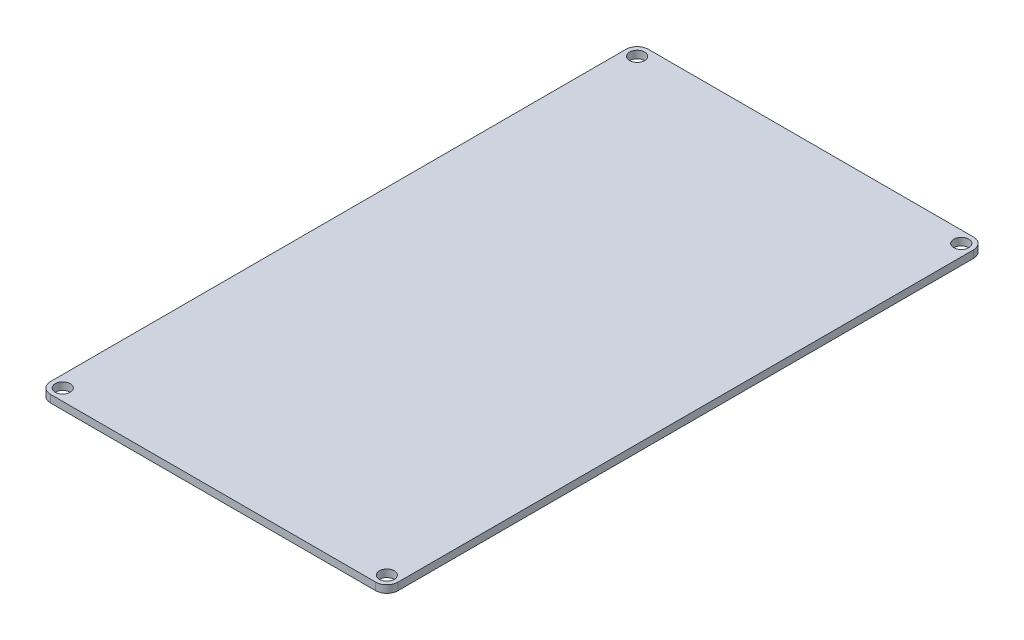
SolidWorks part; units mm, degrees
ref_plane "Front Plane" through (0, 0, 0) normal (0, 0, 1) x (1, 0, 0)
ref_plane "Top Plane" through (0, 0, 0) normal (0, 1, 0) x (1, 0, 0)
ref_plane "Right Plane" through (0, 0, 0) normal (1, 0, 0) x (0, 0, -1)
sketch "Sketch2" plane through (0, 0, 0) normal (0, 1, 0) x (1, 0, 0)
  line L1 (0, 0) -> (93, 0)
  line L2 (0, 0) -> (0, 37.5)
  line L12 (93, 0) -> (93, 160)
  line L17 (95, -2) -> (95, 162)
  line L18 (93, 0) -> (59, 0)
  line L20 (0, 37.5) -> (0, 137.5)
  line L21 (-2, 162) -> (95, 162)
  line L22 (-2, 137.5) -> (-2, 162)
  line L26 (-2, 37.5) -> (-2, 137.5)
  line L28 (0, 137.5) -> (0, 160)
  line L29 (0, 160) -> (93, 160)
  line L34 (-2, -2) -> (-2, 37.5)
  line L43 (-2, -2) -> (95, -2)
  line L44 (46.5, 0) -> (46.5, 160) construction
  line L79 (3.121, 3.121) -> (0, 3.121) construction
  line L80 (3.121, 3.121) -> (3.121, 0) construction
  circle A9 centre (3.121, 3.121) radius 2
  circle A13 centre (89.879, 3.121) radius 2
  circle A14 centre (3.121, 156.879) radius 2
  circle A29 centre (89.879, 156.879) radius 2
  point P41 (2.9756, 2.9756)
  point P50 (3.5491, 3.5491)
  point P51 (3.121, 3.121)
  dimension "D3" = 160
  dimension "D1" = 97
extrude "Boss-Extrude1" add sketch "Sketch2" along normal blind 2
fillet "Fillet13" radius 3 4 edges at (0, 1, 0) (93, 1, 0) (93, 1, -160) (0, 1, -160)
